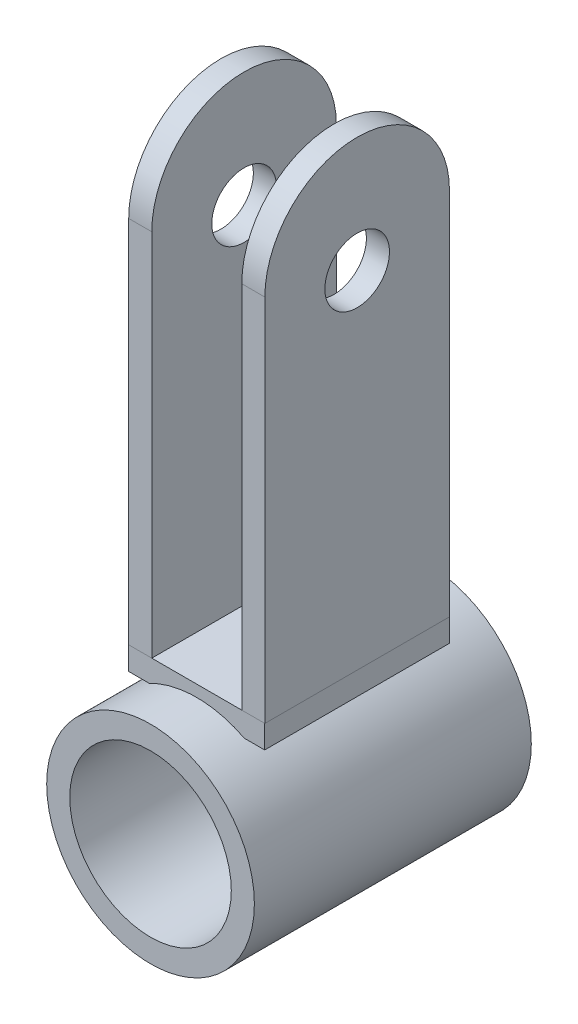
SolidWorks part; units mm, degrees
ref_plane "Front Plane" through (0, 0, 0) normal (0, 0, 1) x (1, 0, 0)
ref_plane "Top Plane" through (0, 0, 0) normal (0, 1, 0) x (1, 0, 0)
ref_plane "Right Plane" through (0, 0, 0) normal (1, 0, 0) x (0, 0, -1)
sketch "Sketch1" plane through (0, 0, 0) normal (0, 0, 1) x (1, 0, 0)
  circle A0 centre (0, 0) radius 17.5
  circle A1 centre (0, 0) radius 22.5
  dimension "D1" = 35
  dimension "D2" = 5
extrude "Boss-Extrude1" add sketch "Sketch1" along normal mid plane 60
ref_plane "Plane2" through (0, 20, 0) normal (0, 1, 0) x (1, 0, 0)
sketch "Sketch6" plane through (0, 20, 0) normal (0, 1, 0) x (1, 0, 0)
  line L1 (14.7311, -20) -> (-14.7311, -20)
  line L2 (14.7311, -20) -> (14.7311, 20)
  line L3 (14.7311, 20) -> (-14.7311, 20)
  line L4 (-14.7311, -20) -> (-14.7311, 20)
  line L5 (14.7311, -20) -> (-14.7311, 20) construction
  line L6 (14.7311, 20) -> (-14.7311, -20) construction
  point P0 (0, 0)
  dimension "D1" = 40
extrude "Boss-Extrude7" add sketch "Sketch6" along normal blind 5
sketch "Sketch7" plane through (0, 25, 0) normal (0, 1, 0) x (1, 0, 0)
  line L0 (-14.7311, -20) -> (14.7311, -20) construction
  line L1 (-14.7311, 20) -> (-9.7311, 20)
  line L2 (-14.7311, 20) -> (-14.7311, -20)
  line L3 (-14.7311, -20) -> (-9.7311, -20)
  line L4 (-9.7311, 20) -> (-9.7311, -20)
  line L5 (0, -1000) -> (0, 49000)
  line L6 (14.7311, -20) -> (9.7311, -20)
  line L7 (9.7311, 20) -> (9.7311, -20)
  line L8 (14.7311, 20) -> (9.7311, 20)
  line L9 (14.7311, 20) -> (14.7311, -20)
  dimension "D1" = 5
sketch "Sketch8" plane through (-14.7311, 0, 0) normal (-1, 0, 0) x (0, 0, 1)
  line L0 (-20, 25) -> (20, 25) construction
  line L1 (-20, 25) -> (20, 25)
  line L2 (-20, 25) -> (20, 25)
  line L3 (-20, 25) -> (-20, 105)
  line L4 (20, 25) -> (20, 105)
  arc A0 (20, 105) -> (-20, 105) centre (0, 105) ccw
  circle A2 centre (0, 100) radius 7
  line M7 (20, 25) -> (-20, 25)
  dimension "D4" = 14
  dimension "D1" = 80
  dimension "D2" = 80
extrude "Boss-Extrude8" add sketch "Sketch8" against normal blind 5 separate body contours L4 A0 L3 A2 M7
pattern_linear "LPattern2" count 2 spacing 24.5 along (1, 0, 0) of "Boss-Extrude8"
